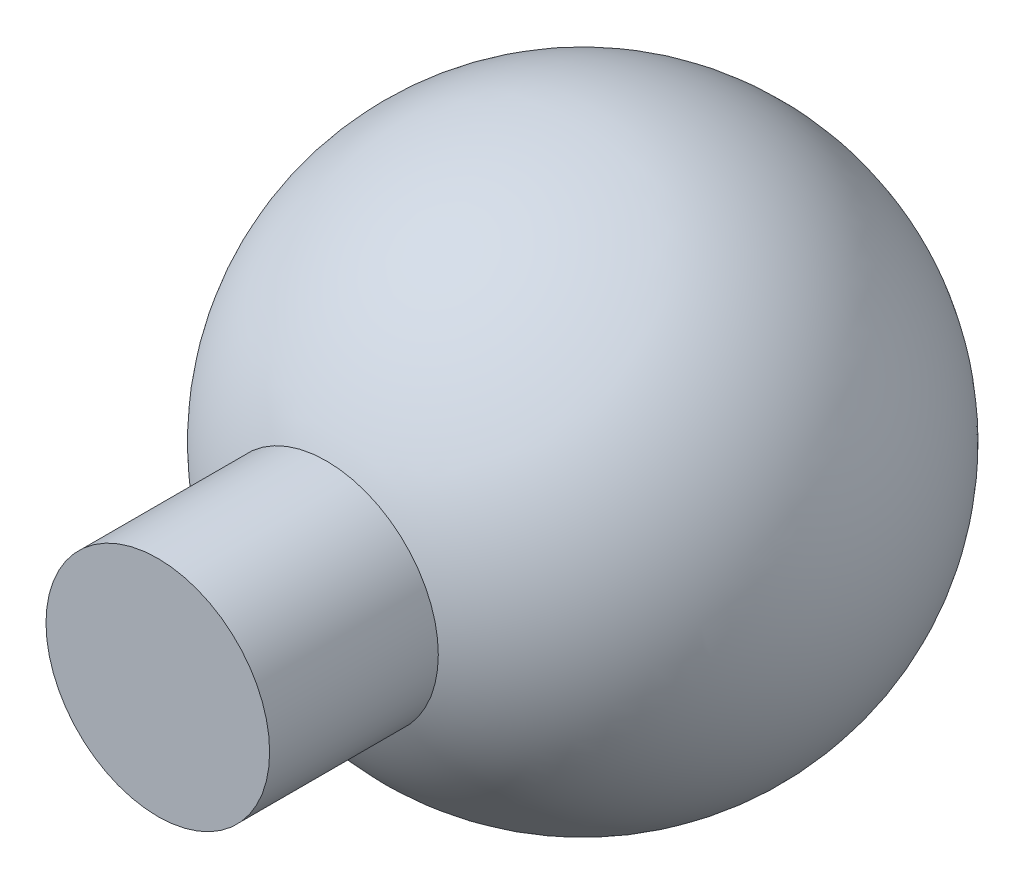
SolidWorks part; units mm, degrees
ref_plane "Front Plane" through (0, 0, 0) normal (0, 0, 1) x (1, 0, 0)
ref_plane "Top Plane" through (0, 0, 0) normal (0, 1, 0) x (1, 0, 0)
ref_plane "Right Plane" through (0, 0, 0) normal (1, 0, 0) x (0, 0, -1)
sketch "Sketch1" plane through (0, 0, 0) normal (0, 1, 0) x (1, 0, 0)
  line L0 (10, 13) -> (10, 15.0871)
  line L1 (0, 0) -> (10, 0)
  line L2 (0, 0) -> (0, 13)
  line L4 (10, 0) -> (10, 13)
  line L5 (0, 13) -> (0, 63)
  arc A0 (0, 13) -> (0, 63) centre (0, 38) ccw
  dimension "D1" = 13
  dimension "D2" = 10
  dimension "D4" = 25
revolve "Revolve1" add sketch "Sketch1" angle 360 about L2
ref_point "Point1"
